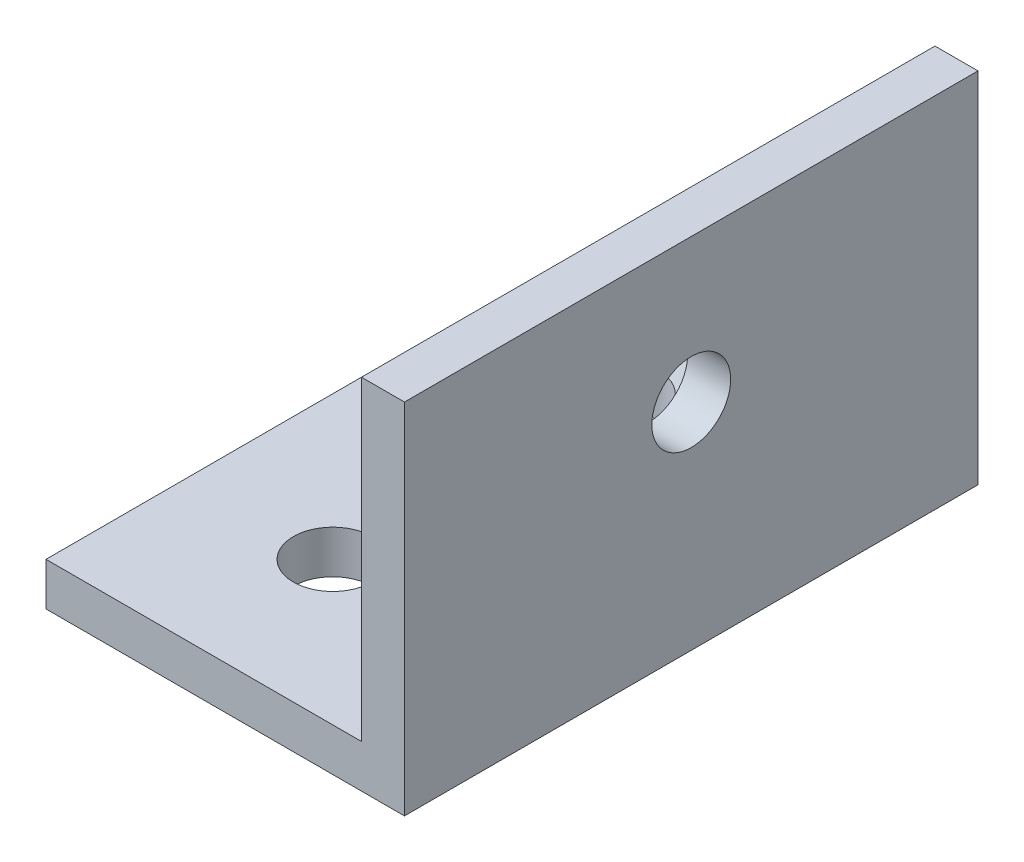
SolidWorks part; units mm, degrees
ref_plane "Front Plane" through (0, 0, 0) normal (0, 0, 1) x (1, 0, 0)
ref_plane "Top Plane" through (0, 0, 0) normal (0, 1, 0) x (1, 0, 0)
ref_plane "Right Plane" through (0, 0, 0) normal (1, 0, 0) x (0, 0, -1)
sketch "Sketch1" plane through (0, 0, 0) normal (0, 0, 1) x (1, 0, 0)
  line L0 (0, 0) -> (0, 25)
  line L1 (0, 25) -> (-3, 25)
  line L2 (-3, 25) -> (-3, 3)
  line L3 (-3, 3) -> (-25, 3)
  line L4 (-25, 3) -> (-25, 0)
  line L5 (-25, 0) -> (0, 0)
  dimension "D1" = 25
  dimension "D2" = 3
  dimension "D3" = 25
extrude "Boss-Extrude1" add sketch "Sketch1" along normal blind 40
sketch "Sketch2" plane through (0, 3, 0) normal (0, 1, 0) x (1, 0, 0)
  line L0 (-3, 0) -> (-25, 0) construction
  line L1 (-25, -40) -> (-25, 0) construction
  line L2 (-25, -20) -> (11.3073, -20) construction
  circle A0 centre (-15, -10) radius 2.75
  circle A2 centre (-15, -30) radius 2.75
  dimension "D3" = 5.5
  dimension "D1" = 10
  dimension "D2" = 10
extrude "Cut-Extrude1" cut sketch "Sketch2" against normal through all
sketch "Sketch3" plane through (-3, 0, 0) normal (-1, 0, 0) x (0, 0, 1)
  line L0 (40, 25) -> (0, 25) construction
  line L1 (40, 25) -> (40, 3) construction
  line L2 (20, 25) -> (20, 0) construction
  circle A0 centre (30, 15) radius 2.5
  circle A1 centre (10, 15) radius 2.5
  dimension "D3" = 5
  dimension "D1" = 10
  dimension "D2" = 10
extrude "Cut-Extrude2" [suppressed] cut sketch "Sketch3" against normal through all
sketch "Sketch4" plane through (-3, 0, 0) normal (-1, 0, 0) x (0, 0, 1)
  line L0 (30, 15) -> (10, 15) construction
  point P4 (20, 15)
hole_wizard "Ø5.0 (5.5) Diameter Hole1" positions "Sketch5" profile "Sketch6" hole size "Ø5.0" standard "ISO" end condition through all
sketch "Sketch5" plane through (-3, 0, 0) normal (-1, 0, 0) x (0, 0, 1)
  point P0 (20, 15)
sketch "Sketch6" plane through (-3, 15, 20) normal (0, 1, 0) x (0, 0, 1)
  line L0 (0, 0) -> (0, 3)
  line L1 (0, 3) -> (2.75, 3)
  line L2 (2.75, 3) -> (2.75, 0)
  line L5 (2.75, 0) -> (0, 0)
  line L11 (0, -6.35) -> (0, 107.95) construction
  dimension "Thru Hole Dia." = 5.5
  dimension "Thru Hole Depth" = 3
